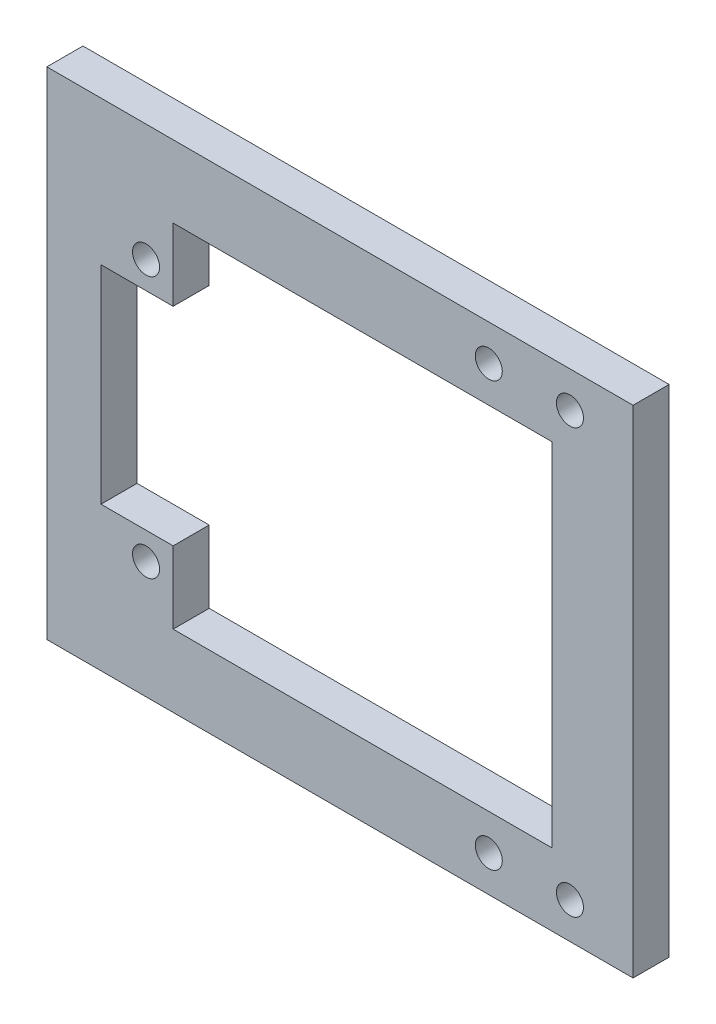
SolidWorks part; units mm, degrees
ref_plane "前视基准面" through (0, 0, 0) normal (0, 0, 1) x (1, 0, 0)
ref_plane "上视基准面" through (0, 0, 0) normal (0, 1, 0) x (1, 0, 0)
ref_plane "右视基准面" through (0, 0, 0) normal (1, 0, 0) x (0, 0, -1)
sketch "草图1" plane through (0, 0, 0) normal (0, 0, 1) x (1, 0, 0)
  line L168 (32.5, 27.5) -> (32.5, -27.5)
  line L169 (32.5, -27.5) -> (-32.5, -27.5)
  line L170 (-32.5, -27.5) -> (-32.5, 27.5)
  line L171 (-32.5, 27.5) -> (32.5, 27.5)
  line L172 (23.5, -19.5) -> (23.5, 19.5)
  line L173 (23.5, 19.5) -> (-18.5, 19.5)
  line L174 (-18.5, 19.5) -> (-18.5, 11.5)
  line L175 (-18.5, 11.5) -> (-26.5, 11.5)
  line L176 (-26.5, 11.5) -> (-26.5, -11.5)
  line L177 (-26.5, -11.5) -> (-18.5, -11.5)
  line L178 (-18.5, -11.5) -> (-18.5, -19.5)
  line L179 (-18.5, -19.5) -> (23.5, -19.5)
  circle A0 centre (-21.5, 14.5) radius 1.5
  circle A1 centre (-21.5, -14.5) radius 1.5
  circle A2 centre (16.5, 23.5) radius 1.5
  circle A3 centre (25.5, 23.5) radius 1.5
  circle A4 centre (16.5, -23.5) radius 1.5
  circle A5 centre (25.5, -23.5) radius 1.5
extrude "凸台-拉伸1" add sketch "草图1" along normal blind 4
